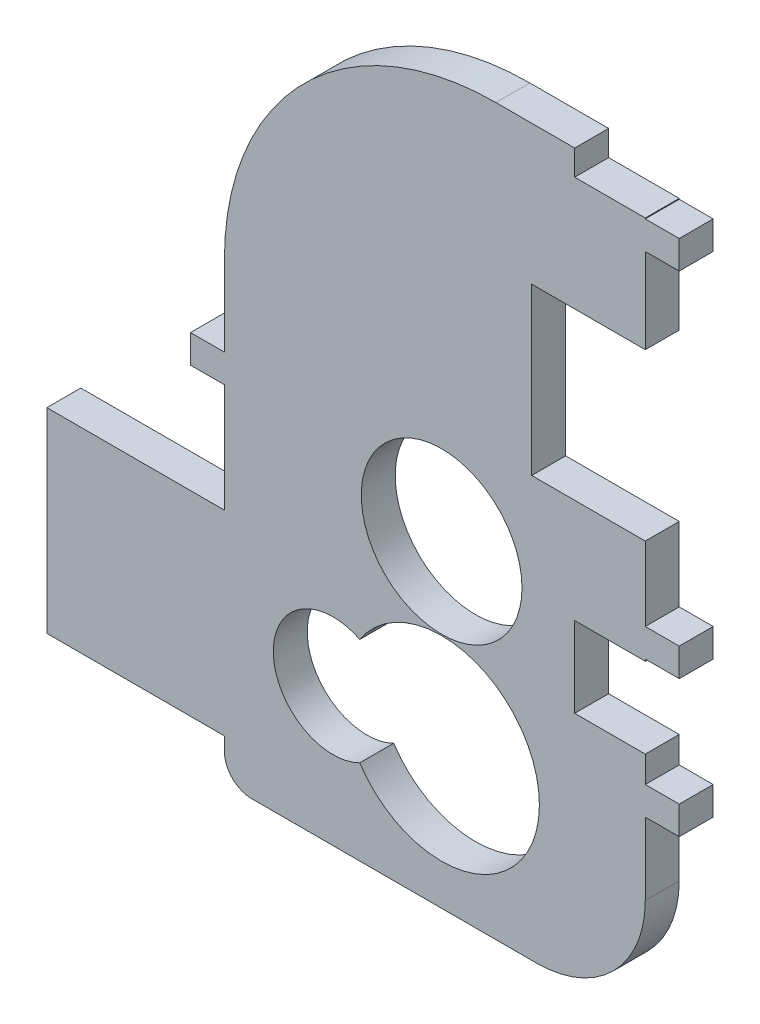
SolidWorks part; units mm, degrees
material "Balsa"
ref_plane "Front Plane" through (0, 0, 0) normal (0, 0, 1) x (1, 0, 0)
ref_plane "Top Plane" through (0, 0, 0) normal (0, 1, 0) x (1, 0, 0)
ref_plane "Right Plane" through (0, 0, 0) normal (1, 0, 0) x (0, 0, -1)
sketch "Sketch1" plane through (0, 0, 0) normal (0, 0, 1) x (1, 0, 0)
  line L0 (0, -1000.1535) -> (0, 48999.8465) construction
  line L1 (-18.4658, -12.954) -> (-18.4658, -3.81) construction
  line L2 (-1000, 0) -> (49000, 0) construction
  line L3 (9.525, 16.51) -> (11.1125, 16.51)
  line L4 (2.54, 19.05) -> (9.525, 19.05)
  line L5 (-10.16, 6.35) -> (-10.16, -14.859)
  line L6 (-10.16, -14.859) -> (9.525, -14.859)
  line L7 (9.525, 19.05) -> (9.525, -14.859)
  line L8 (-11.7475, 1.27) -> (-10.16, 1.27)
  line L9 (-11.7475, 1.27) -> (-11.7475, 2.5908)
  line L10 (-11.7475, 2.5908) -> (-10.16, 2.5908)
  line L11 (-10.16, 1.27) -> (-10.16, 2.5908)
  line L12 (9.525, 0) -> (11.1125, 0)
  line L13 (9.525, 0) -> (9.525, 1.3208)
  line L14 (9.525, 1.3208) -> (11.1125, 1.3208)
  line L15 (11.1125, 0) -> (11.1125, 1.3208)
  line L16 (9.525, 16.51) -> (9.525, 17.8308)
  line L17 (9.525, 17.8308) -> (11.1125, 17.8308)
  line L18 (11.1125, 16.51) -> (11.1125, 17.8308)
  line L19 (-10.16, -12.954) -> (-18.4658, -12.954)
  line L20 (0, -8.382) -> (-5.08, -8.382) construction
  line L22 (9.525, 2.0955) -> (-35.5862, 2.0955) construction
  line L23 (-10.16, -12.954) -> (-10.16, -3.81)
  line L25 (-10.16, -3.81) -> (-18.4658, -3.81)
  line L26 (-18.4658, -12.954) -> (-18.4658, -3.81)
  line L28 (-18.4658, -3.81) -> (0, -3.81) construction
  line L29 (0, -12.954) -> (-18.4658, -12.954) construction
  line L31 (9.525, -5.08) -> (11.1125, -5.08)
  line L32 (9.525, -5.08) -> (9.525, -6.4008)
  line L33 (9.525, -6.4008) -> (11.1125, -6.4008)
  line L34 (11.1125, -5.08) -> (11.1125, -6.4008)
  circle A0 centre (0, 0) radius 3.7592
  arc A3 (2.54, 19.05) -> (-10.16, 6.35) centre (2.54, 6.35) ccw
  arc A4 (-3.829, -10.8803) -> (-3.829, -5.8837) centre (0, -8.382) ccw
  arc A5 (-3.829, -5.8837) -> (-3.829, -10.8803) centre (-5.08, -8.382) ccw
  point P33 (9.525, 2.0955)
  point P35 (-27.4189, 2.0955)
  dimension "D1" = 7.5184
  dimension "D4" = 14.859
  dimension "D3" = 1.27
  dimension "D5" = 1.5875
  dimension "D9" = 12.7
  dimension "D10" = 1.5875
  dimension "D21" = 9.144
  dimension "D23" = 5.588
  dimension "D24" = 8.382
  dimension "D6" = 9.525
  dimension "D7" = 1.3208
  dimension "D8" = 19.685
  dimension "D11" = 19.05
  dimension "D12" = 1.3208
  dimension "D13" = 1.3208
  dimension "D14" = 1.5875
  dimension "D15" = 2
  dimension "D16" = 5.08
  dimension "D19" = 16.51
  dimension "D22" = 5.08
extrude "Boss-Extrude1" add sketch "Sketch1" along normal blind 1.5875
sketch "Sketch2" plane through (0, 0, 1.5875) normal (0, 0, 1) x (1, 0, 0)
  line L1 (6.223, -3.8481) -> (9.525, -3.8481)
  line L2 (6.223, -3.8481) -> (6.223, -0.0889)
  line L3 (6.223, -0.0889) -> (9.525, -0.0889)
  line L4 (9.525, -3.8481) -> (9.525, -0.0889)
  line L5 (9.525, -0.9144) -> (9.525, -3.0226)
  line L7 (9.525, 20.8026) -> (9.525, 18.6944)
  line L9 (6.223, 17.8689) -> (9.525, 17.8689)
  line L10 (6.223, 17.8689) -> (6.223, 21.6281)
  line L11 (6.223, 21.6281) -> (9.525, 21.6281)
  line L12 (9.525, 17.8689) -> (9.525, 21.6281)
  point P8 (9.525, -1.9685)
  point P9 (9.525, -1.9685)
  point P10 (9.525, 19.7485)
  point P15 (9.525, 19.7485)
  line M4 (9.525, 19.05) -> (2.54, 19.05)
  line M11 (-10.16, -14.859) -> (9.525, -14.859)
  line M12 (9.525, -14.859) -> (9.525, -6.4008)
  line M20 (9.525, 17.8308) -> (9.525, 19.05)
  dimension "D1" = 3.7592
  dimension "D2" = 3.302
  dimension "D3" = 3.7592
  dimension "D4" = 3.302
extrude "Cut-Extrude1" cut sketch "Sketch2" against normal up to next contours L3 L2 L4 M11 M12 | L10 L9 M20 M4
sketch "Sketch3" plane through (0, 0, 0) normal (0, 0, -1) x (-1, 0, 0)
  line L4 (-12.5125, 12.5313) -> (-12.5125, 4.7813)
  line L5 (-12.5125, 4.7813) -> (-4.2125, 4.7813)
  line L6 (-4.2125, 4.7813) -> (-4.2125, 12.5313)
  line L7 (-4.2125, 12.5313) -> (-12.5125, 12.5313)
  line L8 (-12.5125, 12.5313) -> (-12.5125, 4.7813)
  line L9 (-12.5125, 4.7813) -> (-4.2125, 4.7813)
  line L10 (-4.2125, 4.7813) -> (-4.2125, 12.5313)
  line L11 (-4.2125, 12.5313) -> (-12.5125, 12.5313)
  line L30 (-6.223, 19.05) -> (-6.223, 17.8689)
  line L31 (-6.223, 17.8689) -> (-9.525, 17.8689)
  line L32 (-9.525, 17.8689) -> (-9.525, 17.8308)
  line L33 (-9.525, 17.8308) -> (-11.1125, 17.8308)
  line L34 (-11.1125, 17.8308) -> (-11.1125, 16.51)
  line L35 (-11.1125, 16.51) -> (-9.525, 16.51)
  line L36 (-9.525, 16.51) -> (-9.525, 1.3208)
  line L37 (-9.525, 1.3208) -> (-11.1125, 1.3208)
  line L38 (-11.1125, 1.3208) -> (-11.1125, 0)
  line L39 (-11.1125, 0) -> (-9.525, 0)
  line L40 (-9.525, 0) -> (-9.525, -0.0889)
  line L41 (-9.525, -0.0889) -> (-6.223, -0.0889)
  line L42 (-6.223, -0.0889) -> (-6.223, -3.8481)
  line L43 (-6.223, -3.8481) -> (-9.525, -3.8481)
  line L44 (-9.525, -3.8481) -> (-9.525, -5.08)
  line L45 (-9.525, -5.08) -> (-11.1125, -5.08)
  line L46 (-11.1125, -5.08) -> (-11.1125, -6.4008)
  line L47 (-11.1125, -6.4008) -> (-9.525, -6.4008)
  line L48 (-9.525, -6.4008) -> (-9.525, -14.859)
  line L49 (-9.525, -14.859) -> (10.16, -14.859)
  line L50 (10.16, -14.859) -> (10.16, -12.954)
  line L51 (10.16, -12.954) -> (18.4658, -12.954)
  line L52 (18.4658, -12.954) -> (18.4658, -3.81)
  line L53 (18.4658, -3.81) -> (10.16, -3.81)
  line L54 (10.16, -3.81) -> (10.16, 1.27)
  line L55 (10.16, 1.27) -> (11.7475, 1.27)
  line L56 (11.7475, 1.27) -> (11.7475, 2.5908)
  line L57 (11.7475, 2.5908) -> (10.16, 2.5908)
  line L58 (10.16, 2.5908) -> (10.16, 6.35)
  line L59 (-2.54, 19.05) -> (-6.223, 19.05)
  line L60 (-6.223, 19.05) -> (-6.223, 17.8689)
  line L61 (-6.223, 17.8689) -> (-9.525, 17.8689)
  line L62 (-9.525, 17.8689) -> (-9.525, 17.8308)
  line L63 (-9.525, 17.8308) -> (-11.1125, 17.8308)
  line L64 (-11.1125, 17.8308) -> (-11.1125, 16.51)
  line L65 (-11.1125, 16.51) -> (-9.525, 16.51)
  line L66 (-9.525, 16.51) -> (-9.525, 1.3208)
  line L67 (-9.525, 1.3208) -> (-11.1125, 1.3208)
  line L68 (-11.1125, 1.3208) -> (-11.1125, 0)
  line L69 (-11.1125, 0) -> (-9.525, 0)
  line L70 (-9.525, 0) -> (-9.525, -0.0889)
  line L71 (-9.525, -0.0889) -> (-6.223, -0.0889)
  line L72 (-6.223, -0.0889) -> (-6.223, -3.8481)
  line L73 (-6.223, -3.8481) -> (-9.525, -3.8481)
  line L74 (-9.525, -3.8481) -> (-9.525, -5.08)
  line L75 (-9.525, -5.08) -> (-11.1125, -5.08)
  line L76 (-11.1125, -5.08) -> (-11.1125, -6.4008)
  line L77 (-11.1125, -6.4008) -> (-9.525, -6.4008)
  line L78 (-9.525, -6.4008) -> (-9.525, -14.859)
  line L79 (-9.525, -14.859) -> (10.16, -14.859)
  line L80 (10.16, -14.859) -> (10.16, -12.954)
  line L81 (10.16, -12.954) -> (18.4658, -12.954)
  line L82 (18.4658, -12.954) -> (18.4658, -3.81)
  line L83 (18.4658, -3.81) -> (10.16, -3.81)
  line L84 (10.16, -3.81) -> (10.16, 1.27)
  line L85 (10.16, 1.27) -> (11.7475, 1.27)
  line L86 (11.7475, 1.27) -> (11.7475, 2.5908)
  line L87 (11.7475, 2.5908) -> (10.16, 2.5908)
  line L88 (10.16, 2.5908) -> (10.16, 6.35)
  line L89 (-2.54, 19.05) -> (-6.223, 19.05)
  arc A1 (10.16, 6.35) -> (-2.54, 19.05) centre (-2.54, 6.35) ccw
  arc A2 (10.16, 6.35) -> (-2.54, 19.05) centre (-2.54, 6.35) ccw
  dimension "D1" = 0
  dimension "D2" = 0
extrude "Cut-Extrude2" cut sketch "Sketch3" against normal up to next contours L10 L11 L8 L9
fillet "Fillet1" radius 5.08 1 edges at (9.525, -14.859, 0.7937)
fillet "Fillet2" radius 1.27 1 edges at (-10.16, -14.859, 0.7937)
